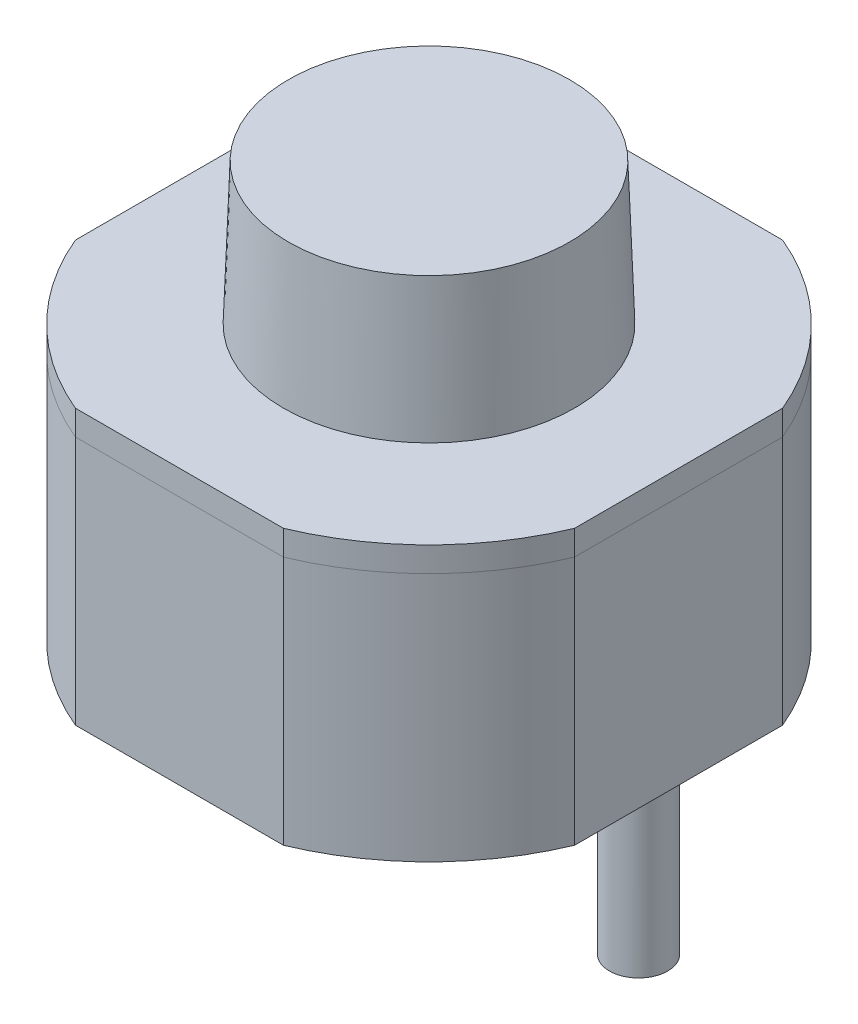
SolidWorks part; units mm, degrees
ref_plane "Piano frontale" through (0, 0, 0) normal (0, 0, 1) x (1, 0, 0)
ref_plane "Piano superiore" through (0, 0, 0) normal (0, 1, 0) x (1, 0, 0)
ref_plane "Piano destro" through (0, 0, 0) normal (1, 0, 0) x (0, 0, -1)
sketch "Schizzo1" plane through (0, 0, 0) normal (0, 1, 0) x (1, 0, 0)
  line L1 (-3, 3) -> (3, 3)
  line L2 (-3, 3) -> (-3, -3)
  line L3 (-3, -3) -> (3, -3)
  line L4 (3, 3) -> (3, -3)
  line L5 (-3, 3) -> (3, -3) construction
  line L6 (-3, -3) -> (3, 3) construction
  point P0 (0, 0)
  dimension "D1" = 6
  dimension "D2" = 6
extrude "Estrusione-Estrusione1" add sketch "Schizzo1" along normal blind 3
sketch "Schizzo2" plane through (0, 3, 0) normal (0, 1, 0) x (1, 0, 0)
  circle A0 centre (0, 0) radius 3.25
  dimension "D1" = 6.5
extrude "Taglio-Estrusione1" cut sketch "Schizzo2" against normal through all flip side to cut
sketch "Schizzo3" plane through (0, 0, 0) normal (0, -1, 0) x (1, 0, 0)
  line L0 (-3.8242, 0) -> (4.328, 0) construction
  line L1 (0, -3.1907) -> (0, 2.061) construction
  circle A0 centre (-2.5189, 0) radius 0.35
  circle A1 centre (2.5189, 0) radius 0.35
  point P7 (0, 0)
  dimension "D1" = 0.7
extrude "Estrusione-Estrusione2" add sketch "Schizzo3" along normal blind 2
sketch "Schizzo4" plane through (0, 3, 0) normal (0, 1, 0) x (1, 0, 0)
  line L4 (-1.25, -3) -> (1.25, -3)
  line L5 (3, -1.25) -> (3, 1.25)
  line L6 (1.25, 3) -> (-1.25, 3)
  line L7 (-3, 1.25) -> (-3, -1.25)
  line L8 (-1.25, -3) -> (1.25, -3)
  line L9 (3, -1.25) -> (3, 1.25)
  line L10 (1.25, 3) -> (-1.25, 3)
  line L11 (-3, 1.25) -> (-3, -1.25)
  arc A4 (1.25, -3) -> (3, -1.25) centre (0, 0) ccw
  arc A5 (3, 1.25) -> (1.25, 3) centre (0, 0) ccw
  arc A6 (-1.25, 3) -> (-3, 1.25) centre (0, 0) ccw
  arc A7 (-3, -1.25) -> (-1.25, -3) centre (0, 0) ccw
  arc A8 (1.25, -3) -> (3, -1.25) centre (0, 0) ccw
  arc A9 (3, 1.25) -> (1.25, 3) centre (0, 0) ccw
  arc A10 (-1.25, 3) -> (-3, 1.25) centre (0, 0) ccw
  arc A11 (-3, -1.25) -> (-1.25, -3) centre (0, 0) ccw
  dimension "D1" = 0
extrude "Estrusione-Estrusione3" add sketch "Schizzo4" along normal blind 0.3 separate body
sketch "Schizzo5" plane through (0, 3.3, 0) normal (0, 1, 0) x (1, 0, 0)
  circle A0 centre (0, 0) radius 1.75
  dimension "D1" = 3.5
extrude "Estrusione-Estrusione4" add sketch "Schizzo5" along normal blind 1.7 draft 2 separate body
